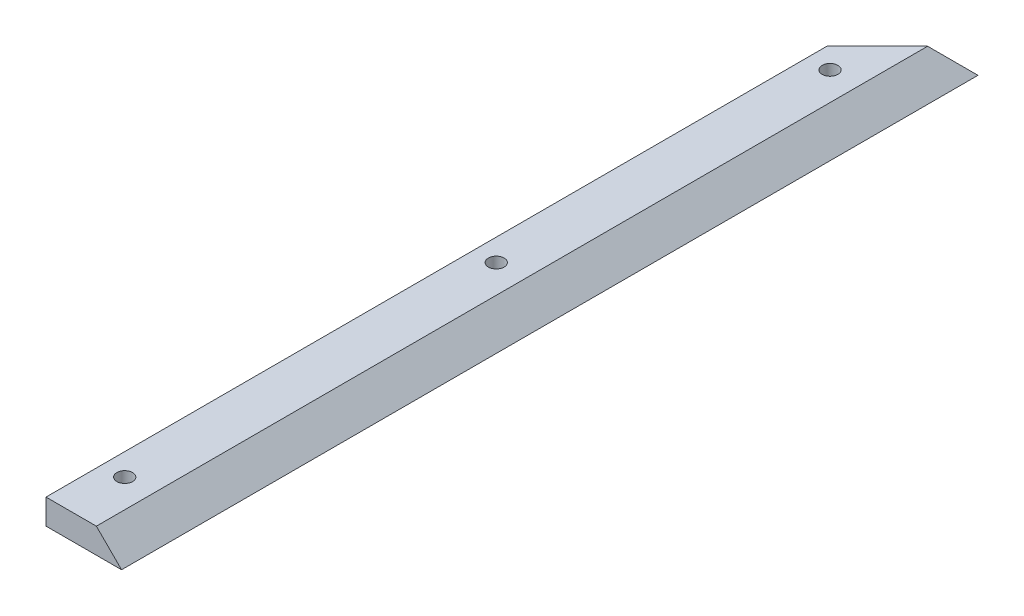
SolidWorks part; units mm, degrees
material "PE High Density"
ref_plane "Front Plane" through (0, 0, 0) normal (0, 0, 1) x (1, 0, 0)
ref_plane "Top Plane" through (0, 0, 0) normal (0, 1, 0) x (1, 0, 0)
ref_plane "Right Plane" through (0, 0, 0) normal (1, 0, 0) x (0, 0, -1)
sketch "Sketch1" plane through (0, 0, 0) normal (0, 0, 1) x (1, 0, 0)
  line L0 (19.05, -6.35) -> (6.35, 6.35)
  line L1 (-19.05, -6.35) -> (19.05, -6.35)
  line L2 (-19.05, -6.35) -> (-19.05, 6.35)
  line L3 (-19.05, 6.35) -> (6.35, 6.35)
  line L5 (-19.05, -6.35) -> (9.525, 3.175) construction
  line L6 (-19.05, 6.35) -> (19.05, -6.35) construction
  point P0 (0, 0)
  dimension "D1" = 12.7
  dimension "D2" = 38.1
  dimension "D3" = 45
extrude "Boss-Extrude1" add sketch "Sketch1" along normal mid plane 431.8
sketch "Sketch2" plane through (0, 6.35, 0) normal (0, 1, 0) x (1, 0, 0)
  line L0 (19.05, -215.9) -> (19.05, 215.9) construction
  line L1 (-19.05, 215.9) -> (19.05, 215.9)
  line L2 (-19.05, 215.9) -> (-19.05, 177.8)
  line L3 (-19.05, 177.8) -> (19.05, 177.8) construction
  line L4 (19.05, 215.9) -> (19.05, 177.8) construction
  line L5 (19.05, 215.9) -> (-19.05, 177.8)
  dimension "D1" = 38.1
extrude "Cut-Extrude1" cut sketch "Sketch2" against normal through all
hole_wizard "5/16 (0.3125) Diameter Hole1" positions "Sketch3" profile "Sketch4" hole size "5/16" standard "ANSI Inch" end condition through all
sketch "Sketch3" plane through (0, 6.35, 0) normal (0, 1, 0) x (1, 0, 0)
  line L1 (6.35, -215.9) -> (-19.05, -215.9) construction
  line L3 (0, 0) -> (-19.05, 0) construction
  line L8 (-19.05, -215.9) -> (-19.05, 177.8) construction
  point P0 (-7.9375, -187.325)
  point P2 (-7.9375, 0)
  point P4 (-7.9375, 168.275)
  dimension "D1" = 28.575
  dimension "D2" = 215.9
  dimension "D3" = 384.175
  dimension "D4" = 11.1125
sketch "Sketch4" plane through (-7.9375, 6.35, 187.325) normal (1, 0, 0) x (0, 0, 1)
  line L0 (0, 0) -> (0, 12.7)
  line L1 (0, 12.7) -> (3.9687, 12.7)
  line L2 (3.9687, 12.7) -> (3.9687, 0)
  line L5 (3.9687, 0) -> (0, 0)
  line L11 (0, -6.35) -> (0, 107.95) construction
  dimension "Thru Hole Dia." = 7.9375
  dimension "Thru Hole Depth" = 12.7
